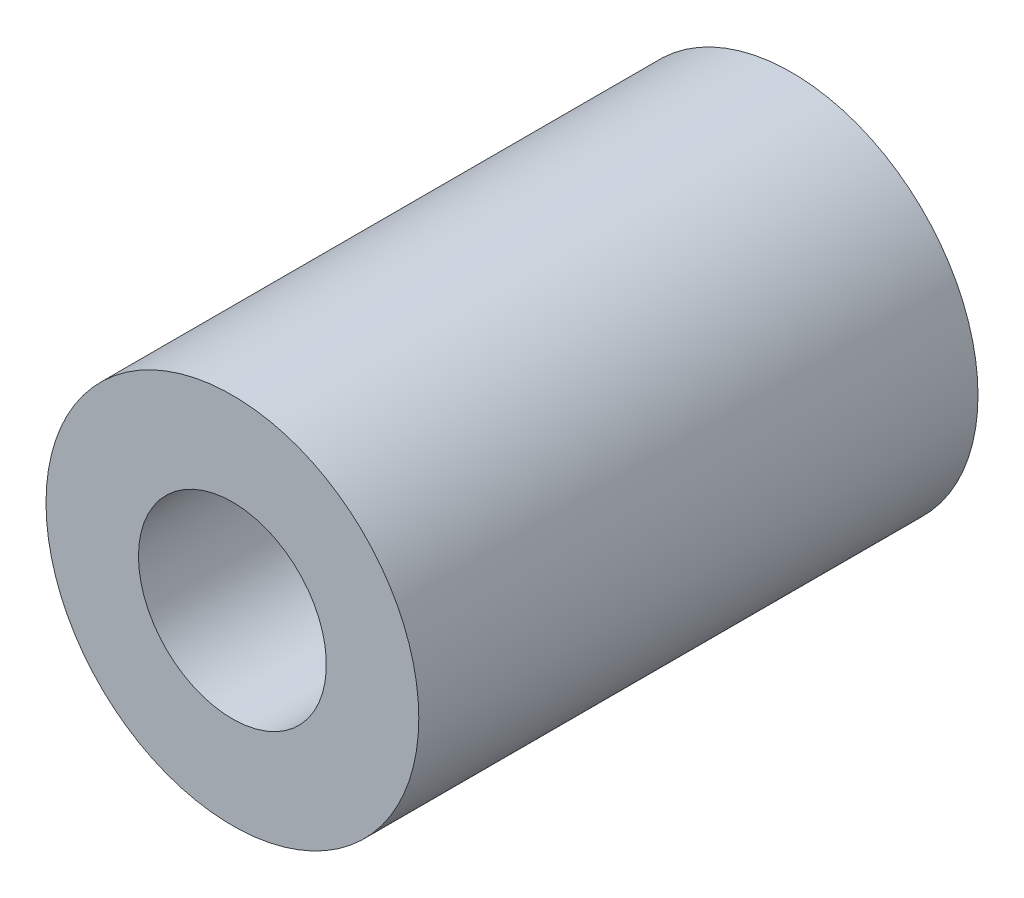
SolidWorks part; units mm, degrees
ref_plane "Front Plane" through (0, 0, 0) normal (0, 0, 1) x (1, 0, 0)
ref_plane "Top Plane" through (0, 0, 0) normal (0, 1, 0) x (1, 0, 0)
ref_plane "Right Plane" through (0, 0, 0) normal (1, 0, 0) x (0, 0, -1)
sketch "Sketch1" plane through (0, 0, 0) normal (0, 0, 1) x (1, 0, 0)
  circle A0 centre (0, 0) radius 6.35
  circle A1 centre (0, 0) radius 3.2004
  dimension "OD" = 12.7
  dimension "ID" = 6.4008
extrude "Extrude1" add sketch "Sketch1" along normal mid plane 19.05
sketch "Sketch2" plane through (0, 0, 0) normal (1, 0, 0) x (0, 0, -1)
  line L0 (-9.525, -3.2004) -> (9.525, -3.2004) construction
  line L3 (9.525, 3.2004) -> (-9.525, 3.2004) construction
  line L5 (-9.525, -3.2004) -> (9.525, -3.2004)
  line L6 (9.525, 3.2004) -> (-9.525, 3.2004)
sketch "Sketch4" plane through (0, 0, 9.525) normal (0, 0, 1) x (1, 0, 0)
  line L0 (0, 0) -> (-2.263, 2.263)
  line L1 (0, -3.4925) -> (0, 3.4925) construction
  circle A0 centre (0, 0) radius 3.2004 construction
  dimension "D1" = 45
